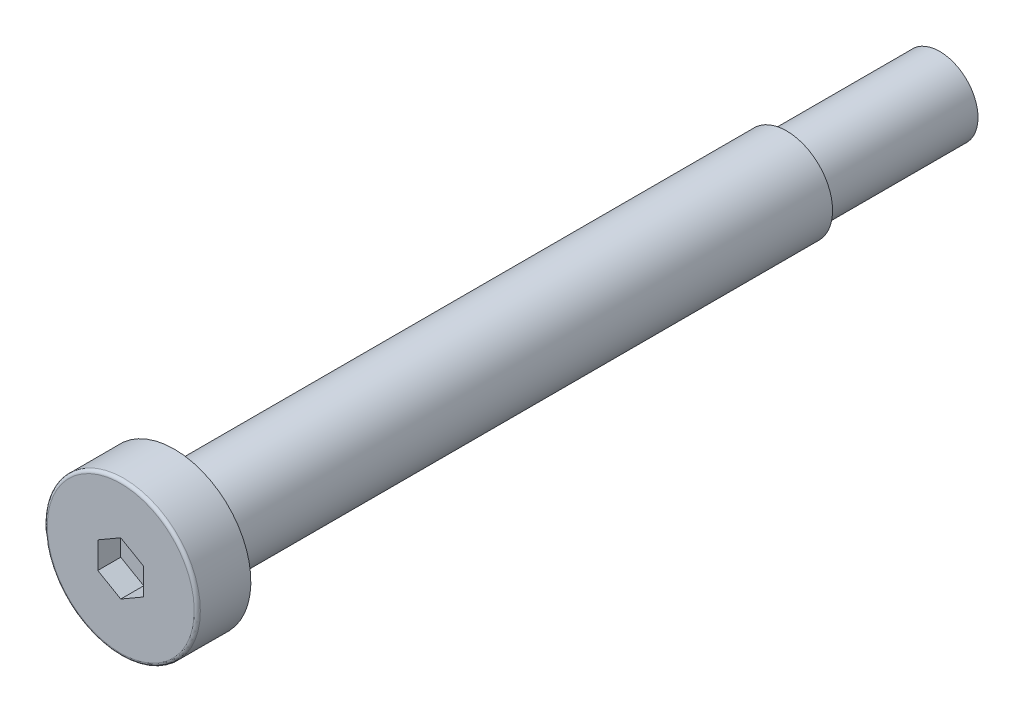
SolidWorks part; units mm, degrees
material "AISI 304"
ref_plane "前视基准面" through (0, 0, 0) normal (0, 0, 1) x (1, 0, 0)
ref_plane "上视基准面" through (0, 0, 0) normal (0, 1, 0) x (1, 0, 0)
ref_plane "右视基准面" through (0, 0, 0) normal (1, 0, 0) x (0, 0, -1)
sketch "草图1" plane through (0, 0, 0) normal (1, 0, 0) x (0, 0, -1)
  line L0 (0, 0) -> (0, 5)
  line L1 (0, 5) -> (3.5, 5)
  line L2 (3.5, 5) -> (3.5, 3)
  line L3 (3.5, 3) -> (43.5, 3)
  line L4 (43.5, 3) -> (43.5, 2.5)
  line L5 (43.5, 2.5) -> (53.5, 2.5)
  line L6 (53.5, 2.5) -> (53.5, 0)
  line L7 (53.5, 0) -> (0, 0) construction
  line L8 (0, 0) -> (53.5, 0)
  dimension "头部厚度" = 3.5
  dimension "头部直径" = 10
  dimension "光杆直径" = 6
  dimension "光杆长度" = 40
  dimension "螺纹直径" = 5
  dimension "螺纹长度" = 10
revolve "旋转1" add sketch "草图1" angle 360 about L7
cosmetic thread "装饰螺纹线1" parameters "D2"=2
sketch "草图2" plane through (0, 0, 0) normal (0, 0, 1) x (1, 0, 0)
  line L1 (1.5, 0.866) -> (0, 1.7321)
  line L2 (0, 1.7321) -> (-1.5, 0.866)
  line L3 (-1.5, 0.866) -> (-1.5, -0.866)
  line L4 (-1.5, -0.866) -> (0, -1.7321)
  line L5 (0, -1.7321) -> (1.5, -0.866)
  line L6 (1.5, -0.866) -> (1.5, 0.866)
  circle A0 centre (0, 0) radius 1.5 construction
  dimension "D1" = 3
extrude "切除-拉伸1" cut sketch "草图2" against normal blind 1.5
fillet "圆角1" radius 0.2 1 edges at (0, 5, 0)
